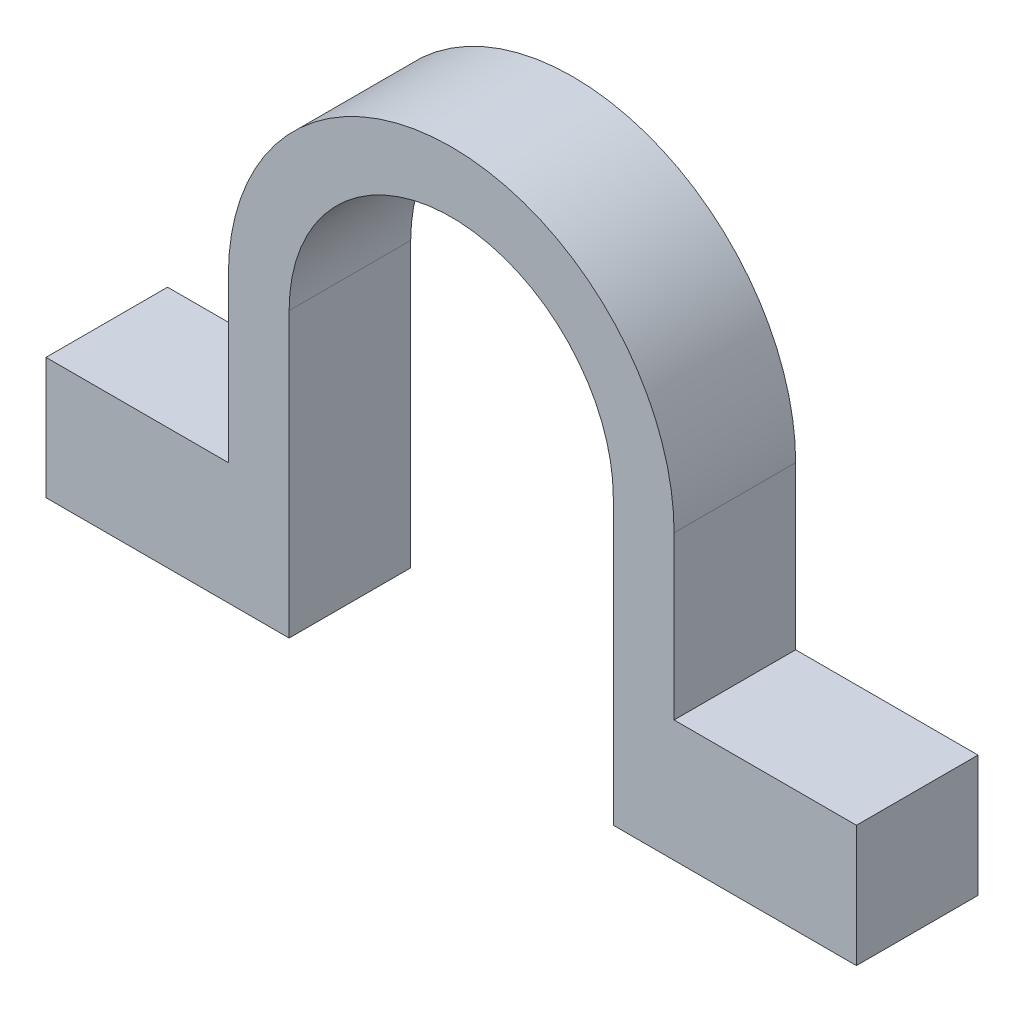
SolidWorks part; units mm, degrees
ref_plane "Front Plane" through (0, 0, 0) normal (0, 0, 1) x (1, 0, 0)
ref_plane "Top Plane" through (0, 0, 0) normal (0, 1, 0) x (1, 0, 0)
ref_plane "Right Plane" through (0, 0, 0) normal (1, 0, 0) x (0, 0, -1)
sketch "Sketch1" plane through (0, 0, 0) normal (0, 0, 1) x (1, 0, 0)
  line L0 (4, -4) -> (7.4799, -4) construction
  line L6 (-4, 0) -> (-4, -7)
  line L8 (4, 0) -> (4, -7)
  line L9 (5.5, -4) -> (10, -4)
  line L10 (10, -4) -> (10, -7)
  line L11 (10, -7) -> (4, -7)
  line L12 (-5.5, -4) -> (-10, -4)
  line L13 (-10, -4) -> (-10, -7)
  line L14 (-10, -7) -> (-4, -7)
  line L15 (-5.5, 0) -> (-5.5, -4)
  line L16 (5.5, 0) -> (5.5, -4)
  arc A0 (4, 0) -> (-4, 0) centre (0, 0) ccw
  arc A1 (5.5, 0) -> (-5.5, 0) centre (0, 0) ccw
  dimension "D1" = 8
  dimension "D2" = 1.5
  dimension "D3" = 3
  dimension "D4" = 3
  dimension "D5" = 6
  dimension "D6" = 6
extrude "Boss-Extrude1" add sketch "Sketch1" along normal blind 3
